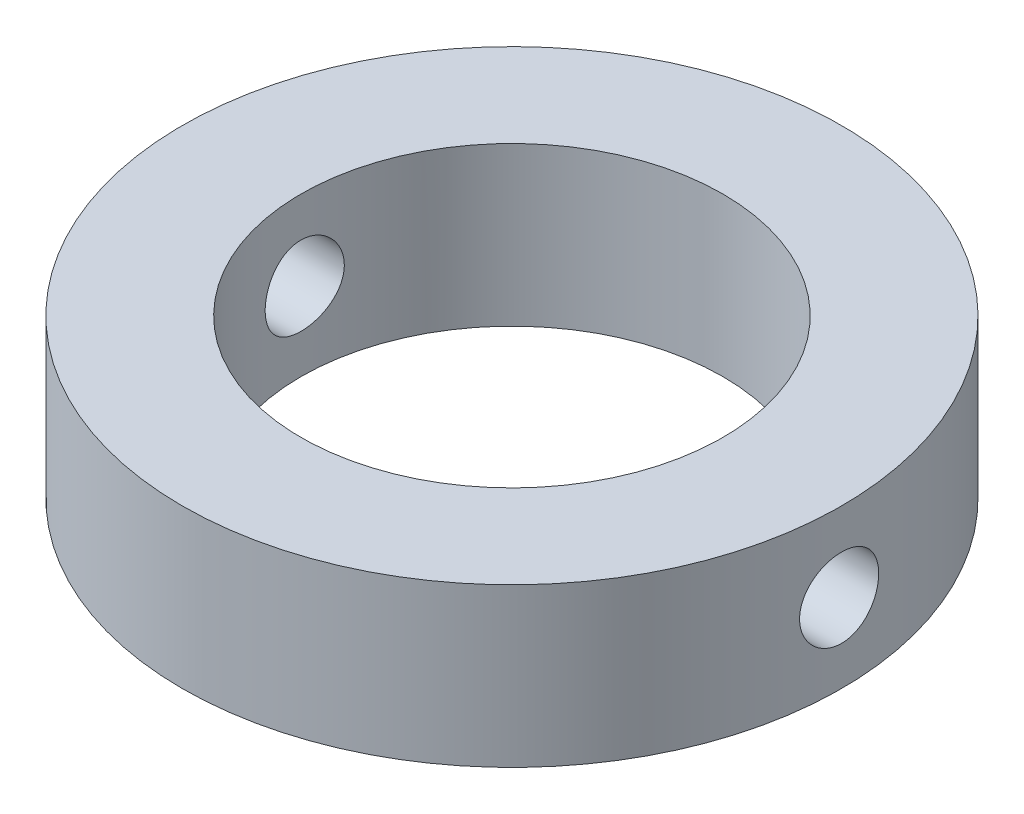
SolidWorks part; units mm, degrees
ref_plane "Front Plane" through (0, 0, 0) normal (0, 0, 1) x (1, 0, 0)
ref_plane "Top Plane" through (0, 0, 0) normal (0, 1, 0) x (1, 0, 0)
ref_plane "Right Plane" through (0, 0, 0) normal (1, 0, 0) x (0, 0, -1)
sketch "Sketch2" plane through (0, 0, 0) normal (0, 1, 0) x (1, 0, 0)
  circle A0 centre (0, 0) radius 25
extrude "Boss-Extrude1" add sketch "Sketch2" along normal blind 12
sketch "Sketch3" plane through (0, 0, 0) normal (1, 0, 0) x (0, 0, -1)
  circle A0 centre (0, 5.9729) radius 3
extrude "Cut-Extrude1" cut sketch "Sketch3" against normal through all both and the other way through all
sketch "Sketch4" plane through (0, 0, 0) normal (0, -1, 0) x (1, 0, 0)
  circle A0 centre (0, 0) radius 16
extrude "Cut-Extrude2" cut sketch "Sketch4" against normal through all both and the other way through all
